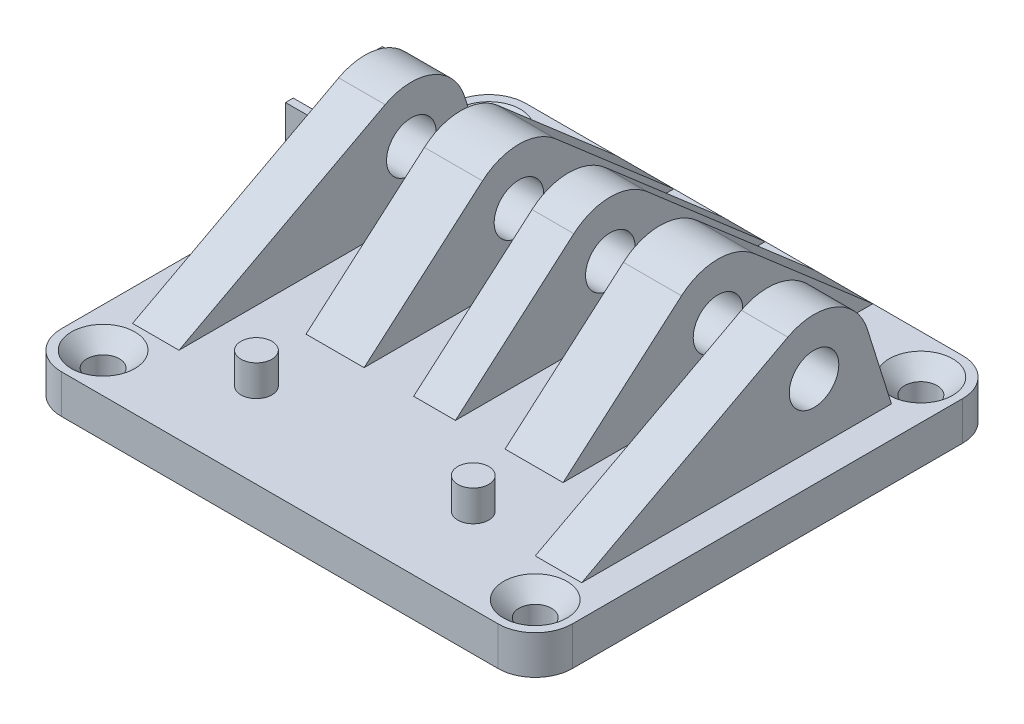
SolidWorks part; units mm, degrees
other "Markup1"
sketch "Sketch13" plane through (0, 20, 0) normal (-0.5335, 0.7333, 0.4215) x (0.8394, 0.3978, 0.3704)
ref_plane "Front Plane" through (0, 0, 0) normal (0, 0, 1) x (1, 0, 0)
ref_plane "Top Plane" through (0, 0, 0) normal (0, 1, 0) x (1, 0, 0)
ref_plane "Right Plane" through (0, 0, 0) normal (1, 0, 0) x (0, 0, -1)
sketch "Sketch4" plane through (0, 0, 0) normal (0, 1, 0) x (1, 0, 0)
  line L0 (33, 60) -> (33, 0) construction
  line L1 (0, 0) -> (66, 0)
  line L2 (0, 0) -> (0, 60)
  line L3 (0, 60) -> (66, 60)
  line L4 (66, 0) -> (66, 60)
  line L6 (30.3, 20) -> (35.7, 20)
  line L7 (30.3, 20) -> (30.3, 60)
  line L8 (30.3, 60) -> (35.7, 60)
  line L9 (35.7, 20) -> (35.7, 60)
  line L10 (30.3, 20) -> (35.7, 60) construction
  line L11 (30.3, 60) -> (35.7, 20) construction
  line L12 (35.7, 60) -> (42.1, 60)
  line L13 (35.7, 60) -> (35.7, 20)
  line L14 (35.7, 20) -> (42.1, 20)
  line L15 (42.1, 60) -> (42.1, 20)
  line L16 (42.1, 20) -> (49.6, 20)
  line L17 (42.1, 20) -> (42.1, 60)
  line L18 (42.1, 60) -> (49.6, 60)
  line L19 (49.6, 20) -> (49.6, 60)
  line L20 (49.6, 60) -> (56, 60)
  line L21 (49.6, 60) -> (49.6, 20)
  line L22 (49.6, 20) -> (56, 20)
  line L23 (56, 60) -> (56, 20)
  line L24 (56, 50) -> (62, 50)
  line L25 (56, 50) -> (56, 10)
  line L26 (56, 10) -> (62, 10)
  line L27 (62, 50) -> (62, 10)
  point P7 (33, 40)
  point P22 (52.8, 20)
  dimension "D1" = 6
  dimension "D2" = 6.4
  dimension "D3" = 7.5
  dimension "D4" = 5.4
  dimension "D5" = 10
  dimension "D6" = 10
  dimension "D7" = 20
  dimension "D8" = 40
  dimension "D9" = 10
  dimension "D10" = 6.4
  dimension "D11" = 66
extrude "Boss-Extrude4" add sketch "Sketch4" along normal blind 5 contours L24 L27 L26 L25 L22 L16 L14 L6 L7 L3 L2 L1 L4 L23 | L15 L3 L9 L14 | L6 L9 L3 L7 | L16 L19 L3 L15 | L23 L3 L19 L22 | L27 L24 L23 L25 L26
sketch "Sketch6" plane through (0, 5, 0) normal (0, 1, 0) x (1, 0, 0)
  line L0 (42.1, 60) -> (49.6, 60) construction
  line L1 (49.6, 20) -> (49.6, 60) construction
  line L2 (49.6, 60) -> (56, 60) construction
  line L3 (56, 60) -> (56, 20) construction
  line L4 (66, 0) -> (66, 60)
  line L5 (66, 60) -> (0, 60)
  line L6 (0, 60) -> (0, 0)
  line L7 (0, 0) -> (66, 0)
  line L8 (66, 0) -> (66, 60)
  line L9 (66, 60) -> (0, 60)
  line L10 (0, 60) -> (0, 0)
  line L11 (0, 0) -> (66, 0)
  line L12 (49.6, 20) -> (56, 20) construction
  line L13 (49.6, 60) -> (49.6, 20) construction
  line L14 (42.1, 20) -> (49.6, 20) construction
  line L15 (35.7, 20) -> (42.1, 20) construction
  line L16 (42.1, 60) -> (42.1, 20) construction
  line L17 (42.1, 20) -> (42.1, 60) construction
  line L18 (35.7, 60) -> (42.1, 60) construction
  line L19 (30.3, 20) -> (35.7, 20) construction
  line L20 (30.3, 20) -> (30.3, 60) construction
  line L21 (30.3, 60) -> (35.7, 60) construction
  line L22 (35.7, 20) -> (35.7, 60) construction
  line L23 (35.7, 60) -> (35.7, 20) construction
  line L24 (0, 0) -> (66, 0) construction
  line L25 (66, 0) -> (66, 60) construction
  line L26 (0, 60) -> (66, 60) construction
  line L27 (0, 0) -> (0, 60) construction
  line L28 (56, 50) -> (62, 50) construction
  line L29 (62, 50) -> (62, 10) construction
  line L30 (56, 10) -> (62, 10) construction
  line L31 (56, 50) -> (56, 10) construction
  line L32 (42.1, 60) -> (49.6, 60)
  line L33 (49.6, 20) -> (49.6, 60)
  line L34 (49.6, 60) -> (56, 60)
  line L35 (56, 60) -> (56, 20)
  line L36 (49.6, 20) -> (56, 20)
  line L37 (49.6, 60) -> (49.6, 20)
  line L38 (42.1, 20) -> (49.6, 20)
  line L39 (35.7, 20) -> (42.1, 20)
  line L40 (42.1, 60) -> (42.1, 20)
  line L41 (42.1, 20) -> (42.1, 60)
  line L42 (35.7, 60) -> (42.1, 60)
  line L43 (30.3, 20) -> (35.7, 20)
  line L44 (30.3, 20) -> (30.3, 60)
  line L45 (30.3, 60) -> (35.7, 60)
  line L46 (35.7, 20) -> (35.7, 60)
  line L47 (35.7, 60) -> (35.7, 20)
  line L48 (0, 0) -> (66, 0)
  line L49 (66, 0) -> (66, 60)
  line L50 (0, 60) -> (66, 60)
  line L51 (0, 0) -> (0, 60)
  line L52 (56, 50) -> (62, 50)
  line L53 (62, 50) -> (62, 10)
  line L54 (56, 10) -> (62, 10)
  line L55 (56, 50) -> (56, 10)
  dimension "D1" = 0
extrude "Boss-Extrude5" add sketch "Sketch6" along normal blind 15 contours L43 L46 L9 L44 | L9 L40 L38 L33 | L35 L55 L54 L53 L52
sketch "Sketch7" plane through (30.3, 0, 0) normal (-1, 0, 0) x (0, 0, 1)
  line L0 (-40, 20) -> (-40, 5) construction
  line L1 (-20, 20) -> (-60, 20) construction
  line L2 (-20, 5) -> (-60, 5) construction
  circle A0 centre (-40, 12.8) radius 3.2
  point P8 (-40, 16)
  dimension "D1" = 6.4
  dimension "D2" = 4
extrude "Cut-Extrude2" cut sketch "Sketch7" against normal through all
sketch "Sketch8" plane through (30.3, 0, 0) normal (-1, 0, 0) x (0, 0, 1)
  line L0 (-20, 5) -> (-35.2856, 18.2419)
  line L1 (-40, 21) -> (-40, 5) construction
  line L2 (-60, 5) -> (-44.7144, 18.2419)
  line L4 (-60, 5) -> (-20, 5)
  line L5 (-20, 5) -> (-20, 20)
  line L6 (-20, 20) -> (-60, 20)
  line L7 (-60, 20) -> (-60, 5)
  line L8 (-60, 5) -> (-20, 5)
  line L9 (-20, 5) -> (-20, 20)
  line L10 (-20, 20) -> (-60, 20)
  line L11 (-60, 20) -> (-60, 5)
  circle A0 centre (-40, 12.8) radius 3.2 construction
  circle A1 centre (-40, 12.8) radius 3.2
  arc A2 (-44.7144, 18.2419) -> (-35.2856, 18.2419) centre (-40, 12.8) cw
  line M10 (-20, 5) -> (-20, 20)
  line M11 (-20, 20) -> (-60, 20)
  line M12 (-60, 20) -> (-60, 5)
  dimension "D1" = 0
extrude "Cut-Extrude3" cut sketch "Sketch8" against normal up to surface (19.3 mm away) contours L2 A2 L10 M12 | A2 L0 M11 M10 up to face at (49.6, 12.8, -36.8)
sketch "Sketch9" plane through (62, 0, 0) normal (1, 0, 0) x (0, 0, -1)
  line L0 (46.8685, 14.9596) -> (50, 5)
  line L1 (10, 5) -> (36.6192, 19.1569)
  line L4 (10, 5) -> (50, 5)
  line L5 (50, 5) -> (50, 20)
  line L6 (50, 20) -> (10, 20)
  line L7 (10, 20) -> (10, 5)
  line L8 (10, 5) -> (50, 5)
  line L9 (50, 5) -> (50, 20)
  line L10 (50, 20) -> (10, 20)
  line L11 (10, 20) -> (10, 5)
  circle A0 centre (40, 12.8) radius 3.2 construction
  circle A1 centre (40, 12.8) radius 3.2
  arc A2 (40, 20) -> (46.8685, 14.9596) centre (40, 12.8) cw
  arc A3 (40, 20) -> (36.6192, 19.1569) centre (40, 12.8) ccw
  line M9 (50, 5) -> (50, 20)
  line M10 (50, 20) -> (10, 20)
  line M11 (10, 20) -> (10, 5)
  dimension "D1" = 0
extrude "Cut-Extrude4" cut sketch "Sketch9" against normal up to next contours A3 L10 L1 M11 | A2 L0 M10 M9
ref_plane "Plane1" through (33, 0, 0) normal (-1, 0, 0) x (0, 0, 1)
mirror "Mirror1" about plane through (33, 0, 0) normal (-1, 0, 0) of "Cut-Extrude4", "Cut-Extrude3", "Cut-Extrude2", "Boss-Extrude5"
sketch "Sketch10" plane through (0, 5, 0) normal (0, 1, 0) x (1, 0, 0)
  line L0 (33, 60) -> (33, 0) construction
  line L1 (60.9, 5.1) -> (5.1, 5.1) construction
  line L2 (60.9, 5.1) -> (60.9, 54.9) construction
  line L3 (60.9, 54.9) -> (5.1, 54.9) construction
  line L4 (5.1, 5.1) -> (5.1, 54.9) construction
  line L5 (60.9, 5.1) -> (5.1, 54.9) construction
  line L6 (60.9, 54.9) -> (5.1, 5.1) construction
  line L9 (0, 60) -> (66, 60) construction
  line L10 (0, 0) -> (0, 60) construction
  circle A0 centre (5.1, 54.9) radius 2.1
  circle A1 centre (60.9, 54.9) radius 2.1
  circle A2 centre (60.9, 5.1) radius 2.1
  circle A3 centre (5.1, 5.1) radius 2.1
  point P0 (33, 30)
  point P9 (5.1, 57)
  point P10 (3, 54.9)
  dimension "D3" = 4.2
  dimension "D1" = 3
  dimension "D2" = 3
extrude "Cut-Extrude5" cut sketch "Sketch10" against normal up to next
chamfer "Chamfer1" distance 2 angle 45 4 edges at (5.1, 5, -3) (60.9, 5, -3) (60.9, 5, -52.8) (5.1, 5, -52.8)
fillet "Fillet1" radius 4.8 4 edges at (66, 2.5, 0) (0, 2.5, 0) (66, 2.5, -60) (0, 2.5, -60)
sketch "Sketch11" plane through (0, 5, 0) normal (0, 1, 0) x (1, 0, 0)
  line L1 (35.7, 36.8) -> (35.7, 43.2) construction
  line L2 (35.7, 36.8) -> (35.7, 43.2)
  line L3 (33, 11) -> (33, -11) construction
  circle A0 centre (47, 11) radius 2
  circle A1 centre (19, 11) radius 2
  point P4 (35.7, 40)
  dimension "D1" = 4
  dimension "D3" = 28
  dimension "D2" = 29
extrude "Boss-Extrude6" add sketch "Sketch11" along normal blind 4 contours A1 | A0
sketch "Sketch12" plane through (4, 0, 0) normal (-1, 0, 0) x (0, 0, 1)
  line L0 (-45.25, 15.8311) -> (-46.25, 15.8311)
  line L1 (-34.75, 15.8311) -> (-40, 18.8622)
  line L2 (-40, 18.8622) -> (-45.25, 15.8311)
  line L3 (-45.25, 15.8311) -> (-45.25, 9.7689)
  line L4 (-45.25, 9.7689) -> (-40, 6.7378)
  line L5 (-40, 6.7378) -> (-34.75, 9.7689)
  line L6 (-34.75, 9.7689) -> (-34.75, 15.8311)
  line L7 (-46.25, 15.8311) -> (-46.25, 5)
  line L8 (-50, 5) -> (-10, 5) construction
  line L9 (-34.75, 15.8311) -> (-33.75, 15.8311)
  line L10 (-33.75, 15.8311) -> (-33.75, 5)
  line L11 (-46.25, 5) -> (-33.75, 5)
  line L12 (-46.25, 15.8311) -> (-45.25, 15.8311)
  line L13 (-34.75, 15.8311) -> (-33.75, 15.8311)
  circle A0 centre (-40, 12.8) radius 3.2 construction
  circle A1 centre (-40, 12.8) radius 3.2
  circle A2 centre (-40, 12.8) radius 5.25 construction
  line M12 (-50, 5) -> (-10, 5)
  dimension "D1" = 10.5
  dimension "D2" = 1
extrude "Boss-Extrude7" add sketch "Sketch12" along normal up to surface (4 mm away) contours L10 L9 L6 L5 L4 L3 L0 L7 M12 up to face at (0, 2.5, -30)
